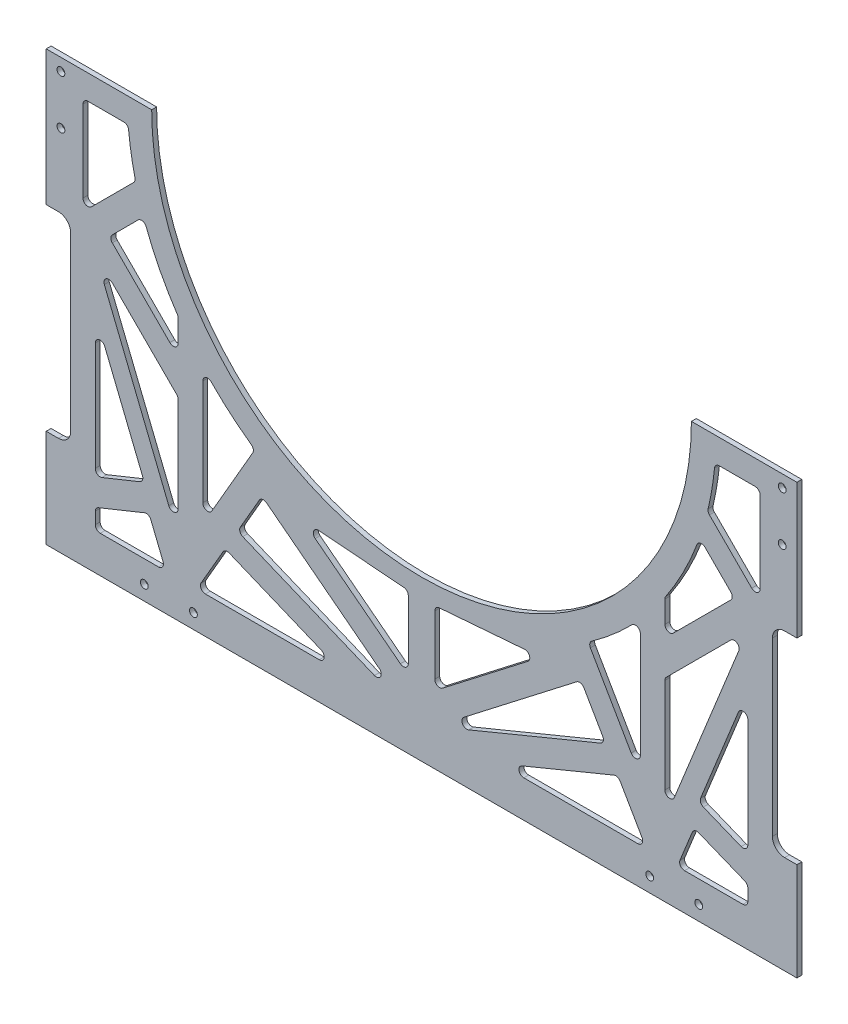
SolidWorks part; units mm, degrees
material "环氧树脂FR-4"
ref_plane "前视基准面" through (0, 0, 0) normal (0, 0, 1) x (1, 0, 0)
ref_plane "上视基准面" through (0, 0, 0) normal (0, 1, 0) x (1, 0, 0)
ref_plane "右视基准面" through (0, 0, 0) normal (1, 0, 0) x (0, 0, -1)
other "环氧"
sketch "草图1" plane through (0, 0, 0) normal (0, 0, 1) x (1, 0, 0)
  line L1 (-153, 87.5) -> (153, 87.5)
  line L2 (-153, 87.5) -> (-153, -87.5)
  line L3 (-153, -87.5) -> (153, -87.5)
  line L4 (153, 87.5) -> (153, -87.5)
  line L5 (-153, 87.5) -> (153, -87.5) construction
  line L6 (-153, -87.5) -> (153, 87.5) construction
  point P0 (0, 0)
  dimension "D1" = 306
  dimension "D2" = 175
extrude "凸台-拉伸1" add sketch "草图1" along normal blind 2
sketch "草图2" plane through (0, 0, 2) normal (0, 0, 1) x (1, 0, 0)
  line L0 (153, 87.5) -> (-153, 87.5) construction
  line L1 (-153, 87.5) -> (-153, -87.5) construction
  line L2 (-153, 32.5) -> (-143, 32.5)
  line L3 (-153, 32.5) -> (-153, -47.5)
  line L4 (-153, -47.5) -> (-143, -47.5)
  line L5 (-143, 32.5) -> (-143, -47.5)
  line L6 (-153, -87.5) -> (153, -87.5) construction
  line L7 (0, -55) -> (0, 55) construction
  line L8 (153, -47.5) -> (143, -47.5)
  line L9 (143, 32.5) -> (143, -47.5)
  line L10 (153, 32.5) -> (143, 32.5)
  line L11 (153, 32.5) -> (153, -47.5)
  circle A0 centre (0, 87.5) radius 110
  dimension "D1" = 220
  dimension "D2" = 0
  dimension "D3" = 40
  dimension "D4" = 80
  dimension "D5" = 10
extrude "切除-拉伸1" cut sketch "草图2" against normal through all
fillet "圆角1" radius 5 4 edges at (143, -47.5, 1) (143, 32.5, 1) (-143, -47.5, 1) (-143, 32.5, 1)
sketch "草图3" plane through (0, 0, 2) normal (0, 0, 1) x (1, 0, 0)
  line L0 (-153, 87.5) -> (-153, 32.5) construction
  line L1 (-110, 87.5) -> (-153, 87.5) construction
  point P0 (-147, 82.5)
  point P6 (-147, 62.5)
  dimension "D1" = 6
  dimension "D2" = 5
  dimension "D4" = 20
  dimension "D3" = 2
hole_wizard "Ø3.2 (3.2) 直径孔1" positions "3D草图1" profile "草图4" hole size "Ø3.2" standard "GB" end condition through all
sketch3d "3D草图1"
  point P0 (-147, 82.5, 2)
  point P3 (-147, 62.5, 2)
sketch "草图4" plane through (-147, 82.5, 2) normal (1, 0, 0) x (0, -1, 0)
  line L0 (0, 0) -> (0, 2)
  line L1 (0, 2) -> (1.6, 2)
  line L2 (1.6, 2) -> (1.6, 0)
  line L5 (1.6, 0) -> (0, 0)
  line L11 (0, -6.35) -> (0, 107.95) construction
  dimension "通孔孔直径" = 3.2
  dimension "通孔孔深度" = 2
mirror "镜向1" about plane through (0, 0, 0) normal (1, 0, 0) of "Ø3.2 (3.2) 直径孔1"
sketch "草图5" plane through (0, 0, 2) normal (0, 0, 1) x (1, 0, 0)
  line L0 (-153, -47.5) -> (-153, -87.5) construction
  line L1 (-153, -87.5) -> (153, -87.5) construction
  point P0 (-113, -81.5)
  point P6 (-93, -81.5)
  dimension "D1" = 40
  dimension "D2" = 6
  dimension "D4" = 20
  dimension "D3" = 2
hole_wizard "Ø3.2 (3.2) 直径孔2" positions "3D草图2" profile "草图6" hole size "Ø3.2" standard "GB" end condition through all
sketch3d "3D草图2"
  point P0 (-113, -81.5, 2)
  point P3 (-93, -81.5, 2)
sketch "草图6" plane through (-113, -81.5, 2) normal (1, 0, 0) x (0, -1, 0)
  line L0 (0, 0) -> (0, 2)
  line L1 (0, 2) -> (1.6, 2)
  line L2 (1.6, 2) -> (1.6, 0)
  line L5 (1.6, 0) -> (0, 0)
  line L11 (0, -6.35) -> (0, 107.95) construction
  dimension "通孔孔直径" = 3.2
  dimension "通孔孔深度" = 2
mirror "镜向2" about plane through (0, 0, 0) normal (1, 0, 0) of "Ø3.2 (3.2) 直径孔2"
sketch "草图7" plane through (0, 0, 2) normal (0, 0, 1) x (1, 0, 0)
  line L0 (-138, 77.5) -> (-138, 37.5)
  line L1 (-153, 87.5) -> (-153, 32.5) construction
  line L3 (-138, 77.5) -> (-119.5826, 77.5)
  line L4 (-110, 87.5) -> (-153, 87.5) construction
  line L5 (-138, 37.5) -> (-116.5534, 58.9466)
  line L6 (-127.4664, 33.8914) -> (-113.3243, 48.0336)
  line L7 (-127.4664, 33.8914) -> (-99.1822, 5.6071)
  line L8 (-99.1822, 5.6071) -> (-99.1822, 19.9508)
  line L9 (-133, 25.2828) -> (-99.1822, -8.535)
  line L10 (-99.1822, -8.535) -> (-99.1822, -58.3023)
  line L11 (-99.1822, -58.3023) -> (-133, 25.2828)
  line L12 (-133, 3.9527) -> (-133, -53.5717)
  line L13 (-133, -53.5717) -> (-113, -45.4799)
  line L14 (-113, -45.4799) -> (-133, 3.9527)
  line L15 (-143, -42.5) -> (-143, 27.5) construction
  line L16 (-133, -64.3592) -> (-133, -72.5)
  line L17 (-133, -72.5) -> (-104.2254, -72.5)
  line L18 (-104.2254, -72.5) -> (-111.1034, -55.5)
  line L19 (-111.1034, -55.5) -> (-133, -64.3592)
  line L20 (-153, -87.5) -> (153, -87.5) construction
  line L21 (-89.1822, 7.2097) -> (-89.1822, -48.3023)
  line L22 (-89.1822, -48.3023) -> (-67.9008, -11.4418)
  line L24 (-91.6057, -72.5) -> (-80.0587, -52.5)
  line L25 (-80.0587, -52.5) -> (-31.6057, -72.5)
  line L26 (-31.6057, -72.5) -> (-91.6057, -72.5)
  line L27 (-75.0147, -43.7636) -> (-65.0147, -26.4431)
  line L28 (-65.0147, -26.4431) -> (-5.3965, -72.5)
  line L29 (-5.3965, -72.5) -> (-75.0147, -43.7636)
  line L31 (-5.3965, -59.8635) -> (-5.3965, -29.8635)
  line L32 (-5.3965, -29.8635) -> (-48.6575, -26.4431)
  line L33 (-48.6575, -26.4431) -> (-5.3965, -59.8635)
  line L34 (-153, -47.5) -> (-153, -87.5) construction
  arc A0 (-119.5826, 77.5) -> (-116.5534, 58.9466) centre (0, 87.5) ccw
  arc A1 (-113.3243, 48.0336) -> (-99.1822, 19.9508) centre (0, 87.5) ccw
  arc A2 (-89.1822, 7.2097) -> (-67.9008, -11.4418) centre (0, 87.5) ccw
  point P40 (-48.6689, -26.4431)
  point P44 (-53.8416, -22.4382)
  dimension "D1" = 240
  dimension "D2" = 15
  dimension "D3" = 10
  dimension "D4" = 40
  dimension "D5" = 45
  dimension "D6" = 10
  dimension "D7" = 40
  dimension "D8" = 20
  dimension "D9" = 10
  dimension "D10" = 10
  dimension "D11" = 0
  dimension "D12" = 17
  dimension "D13" = 8
  dimension "D14" = 20
  dimension "D15" = 10
  dimension "D16" = 15
  dimension "D17" = 10
  dimension "D18" = 10
  dimension "D19" = 30
  dimension "D20" = 10
  dimension "D21" = 10
  dimension "D22" = 15
  dimension "D23" = 20
  dimension "D24" = 60
  dimension "D25" = 10
  dimension "D26" = 20
  dimension "D27" = 10
  dimension "D28" = 0
  dimension "D30" = 0
  dimension "D31" = 10
  dimension "D32" = 30
  dimension "D33" = 0
  dimension "D34" = 20
extrude "切除-拉伸2" cut sketch "草图7" against normal blind 10
fillet "圆角2" radius 2 30 edges at (-5.3965, -59.8635, 1) (-5.3965, -29.8635, 1) (-48.6575, -26.4431, 1) (-75.0147, -43.7636, 1) (-65.0147, -26.4431, 1) (-5.3965, -72.5, 1) (-31.6057, -72.5, 1) (-91.6057, -72.5, 1) (-80.0587, -52.5, 1) (-104.2254, -72.5, 1) (-111.1034, -55.5, 1) (-133, -64.3592, 1) (-133, -72.5, 1) (-133, 3.9527, 1) (-133, -53.5717, 1) (-113, -45.4799, 1) (-89.1822, 7.2097, 1) (-89.1822, -48.3023, 1) (-67.9008, -11.4418, 1) (-99.1822, -58.3023, 1) (-99.1822, -8.535, 1) (-133, 25.2828, 1) (-99.1822, 19.9508, 1) (-99.1822, 5.6071, 1) (-113.3243, 48.0336, 1) (-127.4664, 33.8914, 1) (-116.5534, 58.9466, 1) (-119.5826, 77.5, 1) (-138, 77.5, 1) (-138, 37.5, 1)
mirror "镜向3" about plane through (0, 0, 0) normal (1, 0, 0) of "圆角2", "切除-拉伸2"
